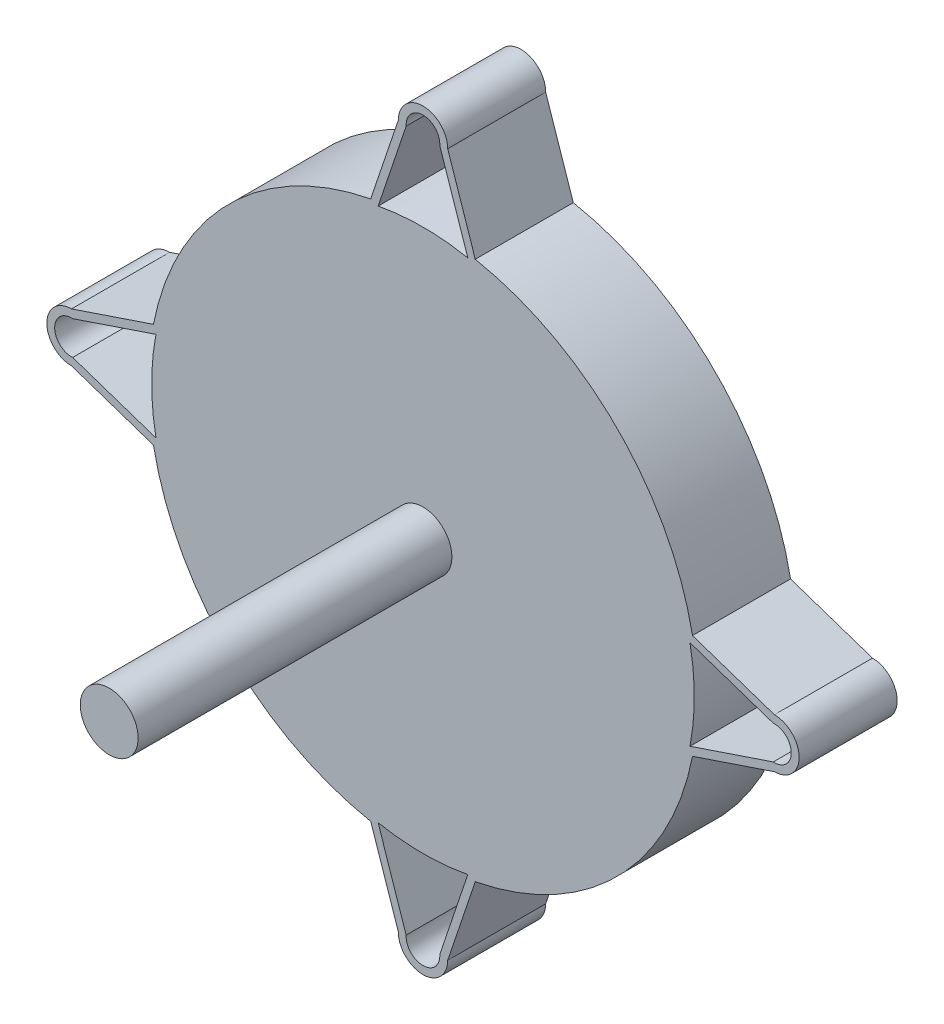
SolidWorks part; units mm, degrees
ref_plane "Front Plane" through (0, 0, 0) normal (0, 0, 1) x (1, 0, 0)
ref_plane "Top Plane" through (0, 0, 0) normal (0, 1, 0) x (1, 0, 0)
ref_plane "Right Plane" through (0, 0, 0) normal (1, 0, 0) x (0, 0, -1)
sketch "Sketch1" plane through (0, 0, 0) normal (0, 0, 1) x (1, 0, 0)
  circle A0 centre (0, 0) radius 70
  dimension "D1" = 140
extrude "Boss-Extrude1" add sketch "Sketch1" along normal blind 25
sketch "Sketch3" plane through (0, 0, 0) normal (0, 0, 1) x (1, 0, 0)
  line L0 (0, 116.6701) -> (0, -143.3934) construction
  line L1 (-127.9492, 0) -> (190.5829, 0) construction
  line L2 (-6.2926, 89.6133) -> (-13.3293, 68.7192)
  line L3 (6.2926, 89.6133) -> (13.3293, 68.7192)
  circle A0 centre (0, 89.6133) radius 6.2926
  circle A1 centre (0, 0) radius 70 construction
  arc A2 (-13.3293, 68.7192) -> (13.3293, 68.7192) centre (0, 0) cw
extrude "Boss-Extrude3" add sketch "Sketch3" along normal blind 25 contours L2 A2 L3 A0 | A0 A2
sketch "Sketch5" plane through (0, 0, 25) normal (0, 0, 1) x (1, 0, 0)
  line L5 (11.4339, 68.0809) -> (4.2823, 89.3162)
  line L6 (-4.2823, 89.3162) -> (-11.4339, 68.0809)
  line L7 (11.4339, 68.0809) -> (4.2823, 89.3162)
  line L8 (-4.2823, 89.3162) -> (-11.4339, 68.0809)
  arc A0 (-11.4339, 68.0809) -> (11.4339, 68.0809) centre (0, 9.1804) cw
  arc A4 (4.2823, 89.3162) -> (-4.2823, 89.3162) centre (0, 89.6133) ccw
  arc A5 (4.2823, 89.3162) -> (-4.2823, 89.3162) centre (0, 89.6133) ccw
  dimension "D2" = 60
  dimension "D1" = 2
extrude "Cut-Extrude1" cut sketch "Sketch5" against normal blind 23
sketch "Sketch6" plane through (0, 0, 2) normal (0, 0, 1) x (1, 0, 0)
  circle A0 centre (0, 89.6133) radius 2.5
  dimension "D1" = 5
extrude "Cut-Extrude2" cut sketch "Sketch6" against normal up to next
pattern_circular "CirPattern2" count 4 over 360 about axis through (0, 0, 0) along (0, 0, 1) of "Boss-Extrude3", "Cut-Extrude1", "Cut-Extrude2"
sketch "Sketch7" plane through (0, 0, 25) normal (0, 0, 1) x (1, 0, 0)
  circle A0 centre (0, 0) radius 7.375
  dimension "D1" = 14.75
extrude "Boss-Extrude4" add sketch "Sketch7" along normal blind 80
